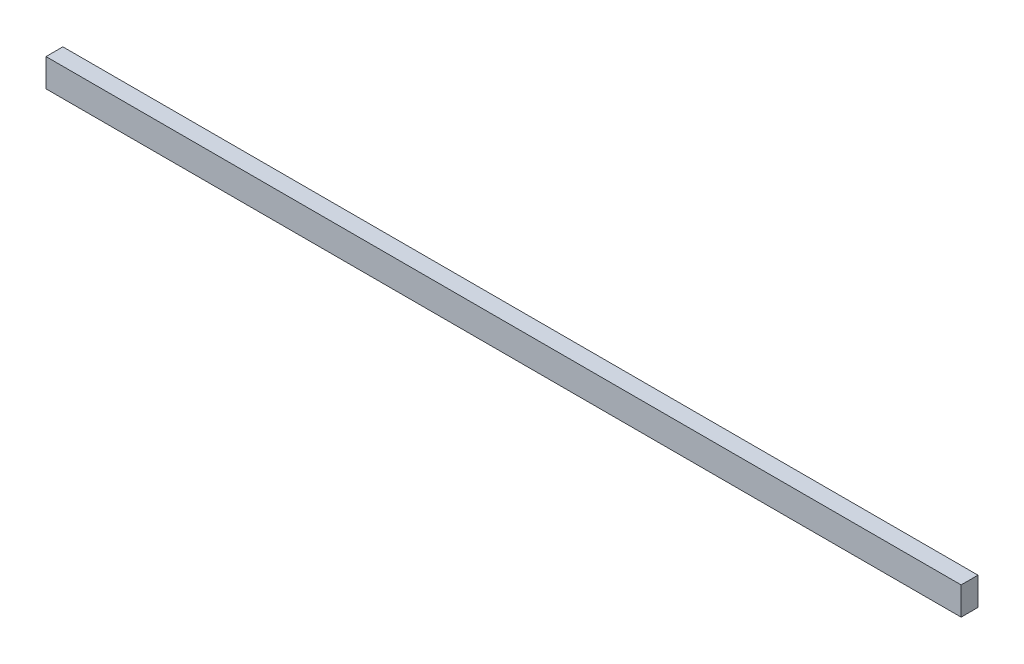
SolidWorks part; units mm, degrees
ref_plane "Front Plane" through (0, 0, 0) normal (0, 0, 1) x (1, 0, 0)
ref_plane "Top Plane" through (0, 0, 0) normal (0, 1, 0) x (1, 0, 0)
ref_plane "Right Plane" through (0, 0, 0) normal (1, 0, 0) x (0, 0, -1)
sketch "Sketch1" plane through (0, 0, 0) normal (0, 0, 1) x (1, 0, 0)
  line L1 (-571.5, 17.4668) -> (571.5, 17.4668)
  line L2 (-571.5, 17.4668) -> (-571.5, -17.4668)
  line L3 (-571.5, -17.4668) -> (571.5, -17.4668)
  line L4 (571.5, 17.4668) -> (571.5, -17.4668)
  line L5 (-571.5, 17.4668) -> (571.5, -17.4668) construction
  line L6 (-571.5, -17.4668) -> (571.5, 17.4668) construction
  point P0 (0, 0)
  point P5 (0, 0)
extrude "Boss-Extrude1" add sketch "Sketch1" along normal blind 8.382 and the other way blind 12.7
